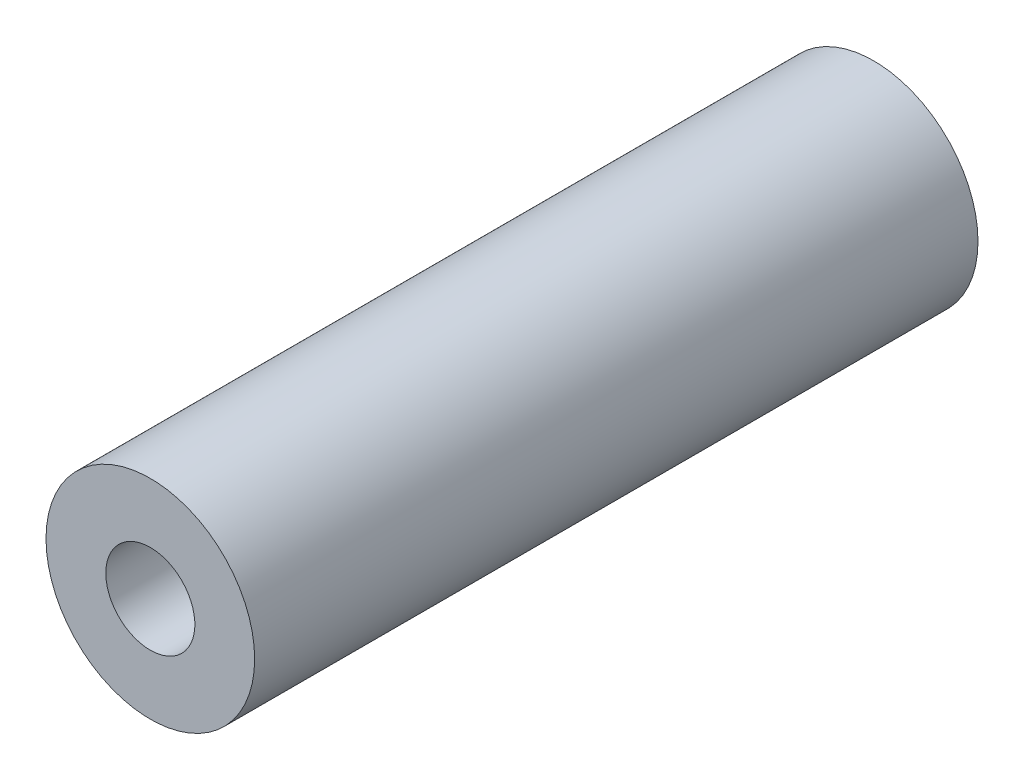
SolidWorks part; units mm, degrees
ref_plane "Front Plane" through (0, 0, 0) normal (0, 0, 1) x (1, 0, 0)
ref_plane "Top Plane" through (0, 0, 0) normal (0, 1, 0) x (1, 0, 0)
ref_plane "Right Plane" through (0, 0, 0) normal (1, 0, 0) x (0, 0, -1)
sketch "Sketch1" plane through (0, 0, 0) normal (0, 0, 1) x (1, 0, 0)
  circle A0 centre (0, 0) radius 3.75
  circle A1 centre (0, 0) radius 1.6
  dimension "D1" = 3.2
  dimension "D2" = 7.5
extrude "Boss-Extrude1" add sketch "Sketch1" along normal blind 26 contours A1 | A0
